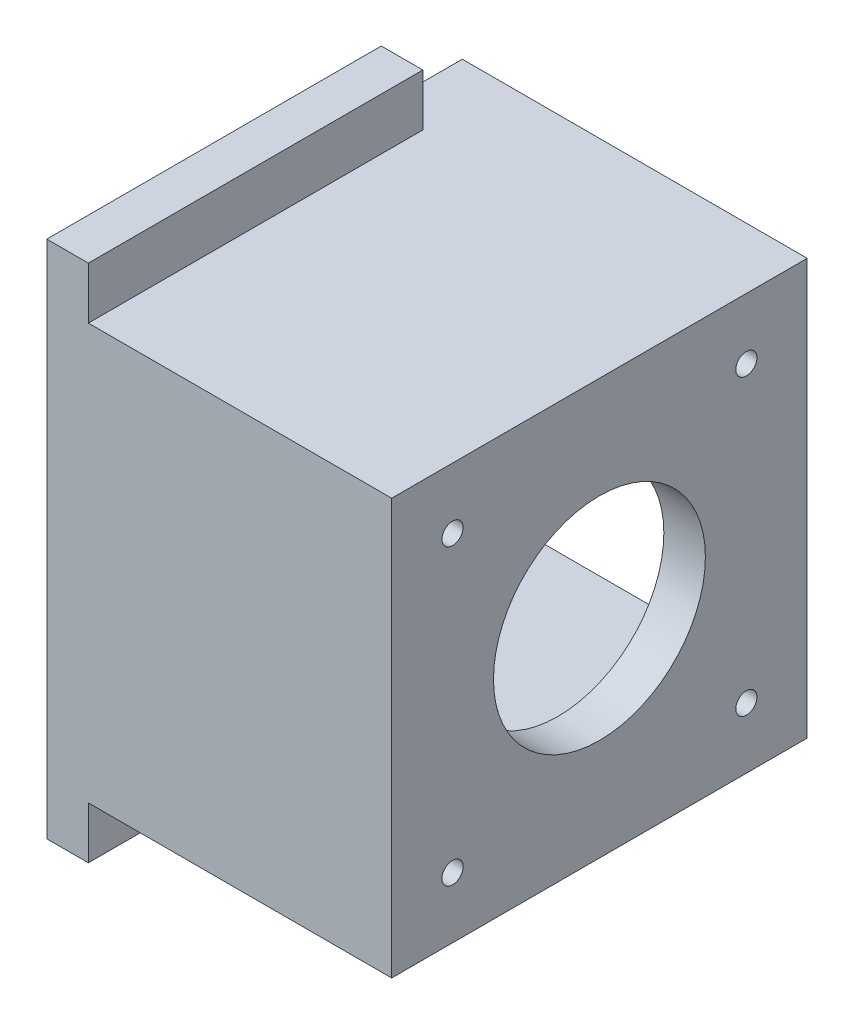
SolidWorks part; units mm, degrees
ref_plane "前视基准面" through (0, 0, 0) normal (0, 0, 1) x (1, 0, 0)
ref_plane "上视基准面" through (0, 0, 0) normal (0, 1, 0) x (1, 0, 0)
ref_plane "右视基准面" through (0, 0, 0) normal (1, 0, 0) x (0, 0, -1)
other "Configuration Table"
sketch "草图1" plane through (0, 0, 0) normal (0, 0, 1) x (1, 0, 0)
  line L0 (20, 225) -> (20, 250)
  line L1 (0, 0) -> (20, 0)
  line L2 (0, 0) -> (0, 250)
  line L3 (0, 250) -> (20, 250)
  line L4 (20, 0) -> (20, 25)
  line L5 (20, 25) -> (166, 25)
  line L7 (20, 225) -> (166, 225)
  line L8 (166, 25) -> (166, 225)
  point P9 (10, 0)
  dimension "D1" = 20
  dimension "D2" = 166
  dimension "D3" = 250
  dimension "D4" = 200
  dimension "D5" = 25
extrude "凸台-拉伸1" add sketch "草图1" against normal blind 200
sketch "草图2" plane through (0, 0, 0) normal (-1, 0, 0) x (0, 0, 1)
  line L0 (-200, 250) -> (-161, 250)
  line L1 (-200, 250) -> (0, 250) construction
  line L2 (-161, 250) -> (-161, 225)
  line L3 (-200, 0) -> (0, 0) construction
  line L4 (-161, 0) -> (-200, 0)
  line L5 (-200, 0) -> (-200, 25)
  line L6 (-161, 25) -> (-161, 0)
  line L11 (-200, 225) -> (-161, 225)
  line L13 (-200, 25) -> (-161, 25)
  line L15 (-200, 225) -> (-200, 250)
  dimension "D1" = 39
  dimension "D2" = 200
extrude "切除-拉伸1" cut sketch "草图2" against normal blind 20
sketch "草图3" plane through (0, 0, -200) normal (0, 0, -1) x (-1, 0, 0)
  line L0 (-166, 25) -> (-166, 225) construction
  line L1 (-146, 202.5833) -> (-20, 202.5833)
  line L2 (-146, 202.5833) -> (-146, 42.5833)
  line L3 (-146, 42.5833) -> (-20, 42.5833)
  line L4 (-20, 202.5833) -> (-20, 42.5833)
  dimension "D1" = 160
  dimension "D2" = 126
  dimension "D3" = 20
extrude "切除-拉伸2" cut sketch "草图3" against normal blind 180
sketch "草图4" plane through (166, 0, 0) normal (1, 0, 0) x (0, 0, -1)
  circle A0 centre (100, 125) radius 51
  point P8 (100, 125)
  dimension "D1" = 102
extrude "切除-拉伸3" cut sketch "草图4" against normal up to next
sketch "草图5" plane through (20, 0, 0) normal (1, 0, 0) x (0, 0, -1)
  circle A0 centre (100, 125) radius 25.5
  dimension "D1" = 51
extrude "切除-拉伸4" cut sketch "草图5" against normal blind 15
sketch "草图6" plane through (0, 0, 0) normal (-1, 0, 0) x (0, 0, 1)
  circle A0 centre (-100, 125) radius 57.15
  point P5 (-100, 125)
  dimension "D1" = 114.3
extrude "切除-拉伸5" cut sketch "草图6" against normal blind 5
sketch "草图7" plane through (20, 0, 0) normal (1, 0, 0) x (0, 0, -1)
  line L0 (0, 125) -> (325.7801, 125) construction
  line L1 (0, 25) -> (0, 225) construction
  circle A0 centre (20, 240) radius 4.5
  circle A1 centre (80.5, 240) radius 4.5
  circle A2 centre (141, 240) radius 4.5
  circle A3 centre (141, 10) radius 4.5
  circle A4 centre (80.5, 10) radius 4.5
  circle A5 centre (20, 10) radius 4.5
  point P7 (20, 240)
  dimension "D1" = 9
  dimension "D2" = 3
extrude "切除-拉伸6" [suppressed] cut sketch "草图7" against normal up to next
sketch "草图8" plane through (166, 0, 0) normal (1, 0, 0) x (0, 0, -1)
  circle A0 centre (100, 125) radius 100 construction
  point P14 (170.71, 195.7114)
  dimension "D1" = 200
hole_wizard "M12 螺纹孔1" positions "草图8" profile "草图9" tap size "M12" standard "GB"
sketch "草图9" plane through (166, 195.7114, -170.71) normal (0, 1, 0) x (0, 0, -1)
  line L0 (0, 0) -> (0, 29.25)
  line L1 (0, 29.25) -> (5.1, 26.1856)
  line L2 (5.1, 26.1856) -> (5.1, 0)
  line L5 (5.1, 0) -> (0, 0)
  line L10 (0, 29.25) -> (-5.1, 26.1856) construction
  line L11 (0, -6.35) -> (0, 107.95) construction
  dimension "螺纹孔钻头直径" = 10.2
  dimension "螺纹孔钻头深度" = 29.25
  dimension "导头角度" = 118
cosmetic thread "孔螺纹线1" parameters "D1"=24, "D2"=12
pattern_circular "阵列(圆周)1" count 4 every 90 about axis through (0, 125, -100) along (1, 0, 0) of "M12 螺纹孔1"
